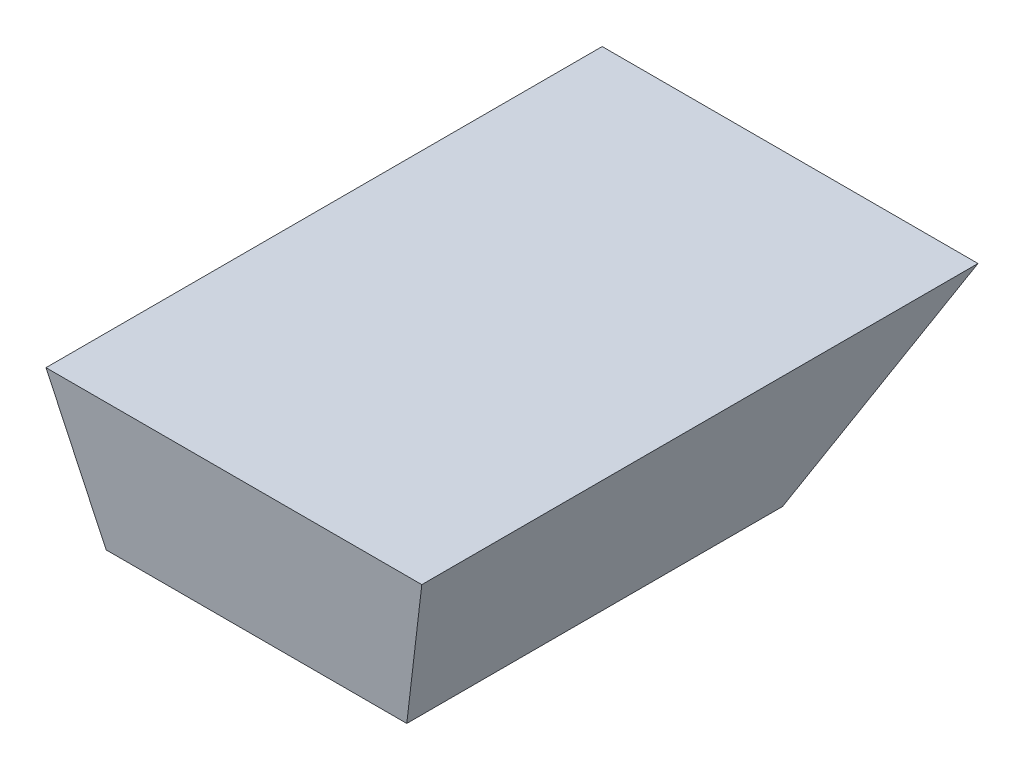
SolidWorks part; units mm, degrees
ref_plane "前基準面" through (0, 0, 0) normal (0, 0, 1) x (1, 0, 0)
ref_plane "上基準面" through (0, 0, 0) normal (0, 1, 0) x (1, 0, 0)
ref_plane "右基準面" through (0, 0, 0) normal (1, 0, 0) x (0, 0, -1)
sketch "草圖1" plane through (0, 0, 0) normal (0, 0, 1) x (1, 0, 0)
  line L1 (-125, 50) -> (125, 50)
  line L2 (-125, 50) -> (-125, -50)
  line L3 (-125, -50) -> (125, -50)
  line L4 (125, 50) -> (125, -50)
  dimension "D1" = 100
  dimension "D2" = 50
  dimension "D3" = 125
  dimension "D4" = 250
extrude "填料-伸長1" add sketch "草圖1" along normal blind 370
sketch "草圖2" plane through (0, 0, 370) normal (0, 0, 1) x (1, 0, 0)
  line L0 (0, 50) -> (0, -50) construction
  line L1 (125, 50) -> (-125, 50) construction
  line L2 (-125, -50) -> (125, -50) construction
  line L3 (-125, 50) -> (-100, -50)
  line L4 (-100, -50) -> (-125, -50)
  line L5 (-125, -50) -> (-125, 50)
  line L6 (125, 50) -> (125, -50)
  line L7 (125, -50) -> (100, -50)
  line L8 (100, -50) -> (125, 50)
  dimension "D1" = 25
  dimension "D2" = 25
extrude "除料-伸長1" cut sketch "草圖2" against normal blind 370
ref_plane "平面4" through (-125, 50, 370) normal (-1, 0, 0) x (0, 0, 1)
sketch "草圖7" plane through (-125, 50, 370) normal (-1, 0, 0) x (0, 0, 1)
  line L0 (0, 0) -> (-15, -100)
  line L1 (-370, -100) -> (0, -100) construction
  line L2 (-15, -100) -> (0, -100)
  line L3 (0, -100) -> (0, 0)
  line L4 (-370, 0) -> (-265, -100)
  line L5 (-265, -100) -> (-370, -100)
  line L6 (-370, -100) -> (-370, 0)
  dimension "D1" = 250
  dimension "D2" = 105
extrude "除料-伸長3" cut sketch "草圖7" against normal through all
